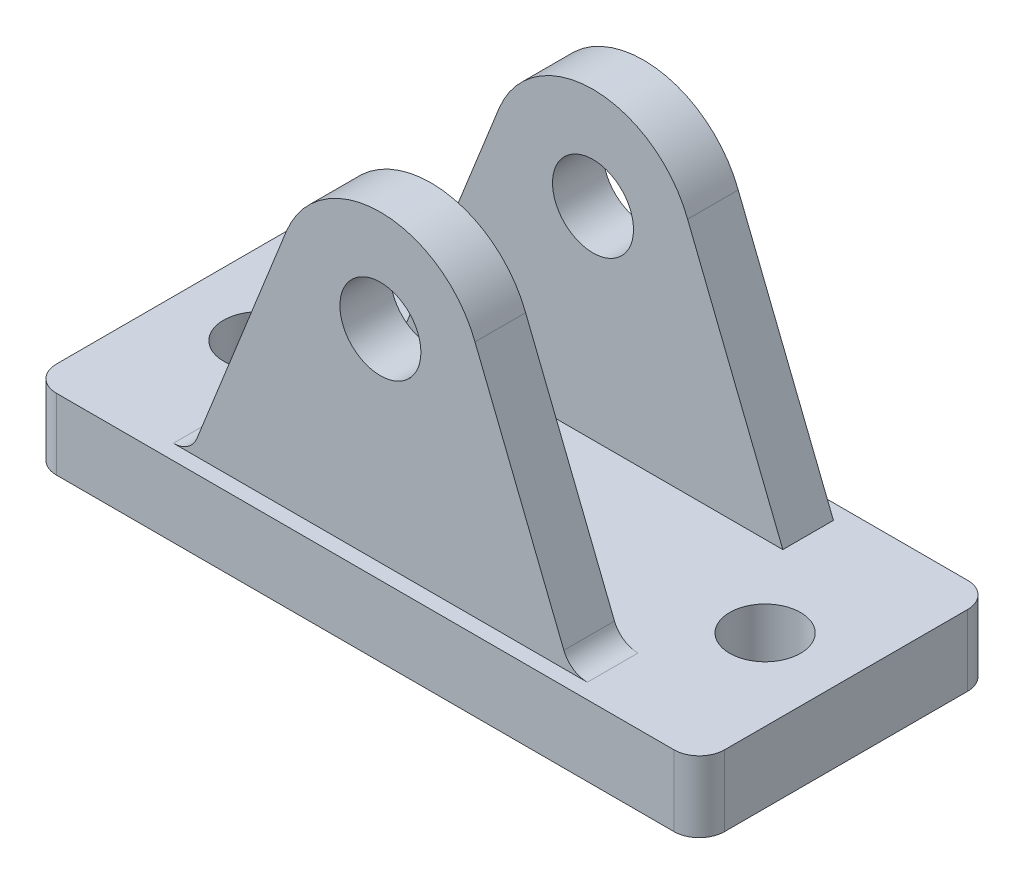
SolidWorks part; units mm, degrees
ref_plane "Ön Düzlem" through (0, 0, 0) normal (0, 0, 1) x (1, 0, 0)
ref_plane "Üst Düzlem" through (0, 0, 0) normal (0, 1, 0) x (1, 0, 0)
ref_plane "Sağ Düzlem" through (0, 0, 0) normal (1, 0, 0) x (0, 0, -1)
sketch "Çizim1" plane through (0, 0, 0) normal (0, 1, 0) x (1, 0, 0)
  line L1 (-135.2258, 45.4032) -> (-13.2258, 45.4032)
  line L2 (-140.2258, 40.4032) -> (-140.2258, -7.5968)
  line L3 (-135.2258, -12.5968) -> (-13.2258, -12.5968)
  line L4 (-8.2258, 40.4032) -> (-8.2258, -7.5968)
  circle A0 centre (-124.2258, 16.4032) radius 7
  circle A1 centre (-24.2258, 16.4032) radius 7
  arc A2 (-13.2258, 45.4032) -> (-8.2258, 40.4032) centre (-13.2258, 40.4032) cw
  arc A3 (-140.2258, -7.5968) -> (-135.2258, -12.5968) centre (-135.2258, -7.5968) ccw
  arc A4 (-13.2258, -12.5968) -> (-8.2258, -7.5968) centre (-13.2258, -7.5968) ccw
  arc A5 (-135.2258, 45.4032) -> (-140.2258, 40.4032) centre (-135.2258, 40.4032) ccw
  point P10 (-8.2258, 45.4032)
  point P15 (-8.2258, -12.5968)
  point P18 (-140.2258, 45.4032)
  dimension "D5" = 14
  dimension "D6" = 14
  dimension "D8" = 5
  dimension "D1" = 132
  dimension "D2" = 58
  dimension "D3" = 16
  dimension "D4" = 16
  dimension "D7" = 100
extrude "Yükseklik-Ekstrüzyon1" add sketch "Çizim1" along normal blind 14
sketch "Çizim5" plane through (0, 0, 12.5968) normal (0, 0, 1) x (1, 0, 0)
  line L0 (-92.8008, 61.4141) -> (-111.7258, 14)
  line L1 (-135.2258, 14) -> (-13.2258, 14) construction
  line L2 (-55.5367, 61.1216) -> (-36.7258, 14)
  line L3 (-135.2258, 0) -> (-13.2258, 0) construction
  line L4 (-140.2258, 14) -> (-140.2258, 0) construction
  arc A0 (-55.5367, 61.1216) -> (-92.8008, 61.4141) centre (-74.2258, 54) ccw
  circle A1 centre (-74.2258, 54) radius 8
  line M5 (-13.2258, 14) -> (-135.2258, 14)
  dimension "D1" = 40
  dimension "D2" = 16
  dimension "D3" = 54
  dimension "D4" = 75
  dimension "D5" = 37.5
  dimension "D6" = 28.5
extrude "Yükseklik-Ekstrüzyon3" add sketch "Çizim5" against normal blind 10 from offset 3 contours L2 A0 L0 A1 M5 offset against normal yes
fillet "Radyus1" radius 5 2 edges at (-36.7258, 14, 4.5968) (-111.7258, 14, 4.5968)
ref_plane "Düzlem3" through (0, 0, -16.4032) normal (0, 0, 1) x (1, 0, 0)
pattern_linear "LÇoğaltma1" count 2 spacing 42 along (0, 0, -1) of "Yükseklik-Ekstrüzyon3"
